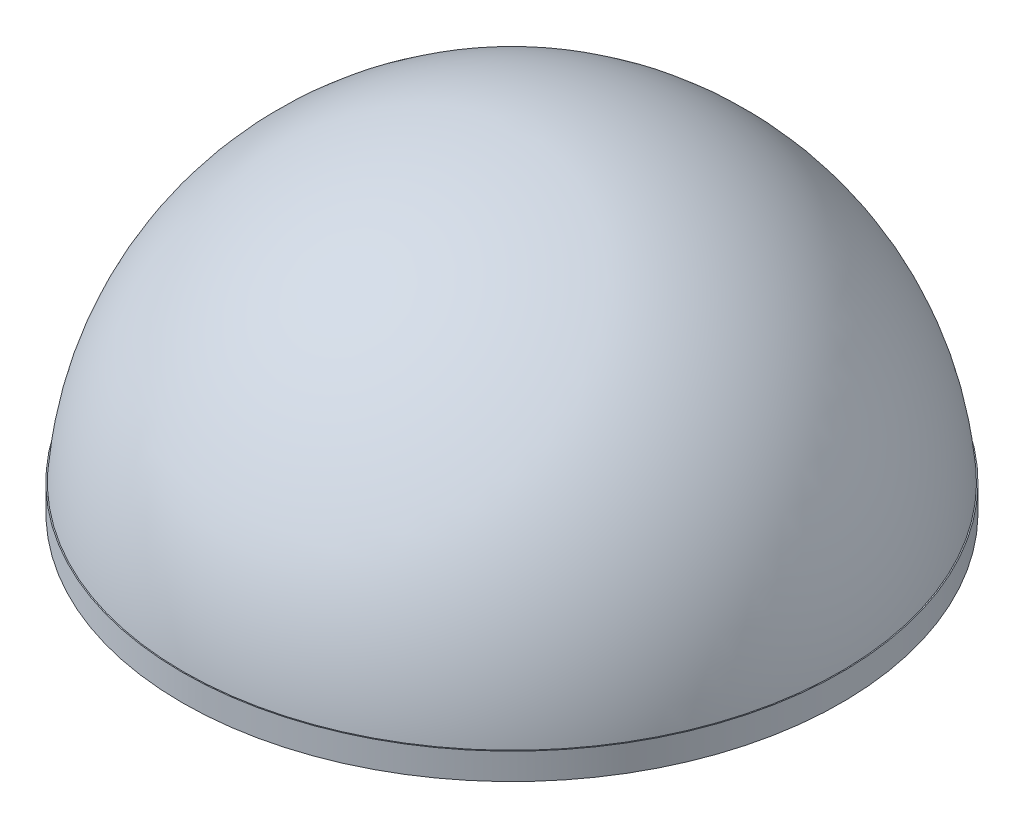
SolidWorks part; units mm, degrees
ref_plane "Front Plane" through (0, 0, 0) normal (0, 0, 1) x (1, 0, 0)
ref_plane "Top Plane" through (0, 0, 0) normal (0, 1, 0) x (1, 0, 0)
ref_plane "Right Plane" through (0, 0, 0) normal (1, 0, 0) x (0, 0, -1)
sketch "Sketch1" plane through (0, 0, 0) normal (0, 1, 0) x (1, 0, 0)
  line L0 (0, 31.75) -> (0, -31.75) construction
  line L1 (0, 31.75) -> (0, -31.75)
  arc A0 (0, -31.75) -> (0, 31.75) centre (0, 0) ccw
  dimension "D1" = 63.5
revolve "Revolve1" add sketch "Sketch1" angle 180 about L0
shell "Shell1" thickness 1.27
sketch "Sketch6" plane through (0, 0, 0) normal (0, 1, 0) x (1, 0, 0)
  circle A0 centre (0, 0) radius 31.75
  circle A1 centre (0, 0) radius 30.48
  dimension "D1" = 63.5
  dimension "D2" = 60.96
extrude "Boss-Extrude1" add sketch "Sketch6" along normal blind 2.54
